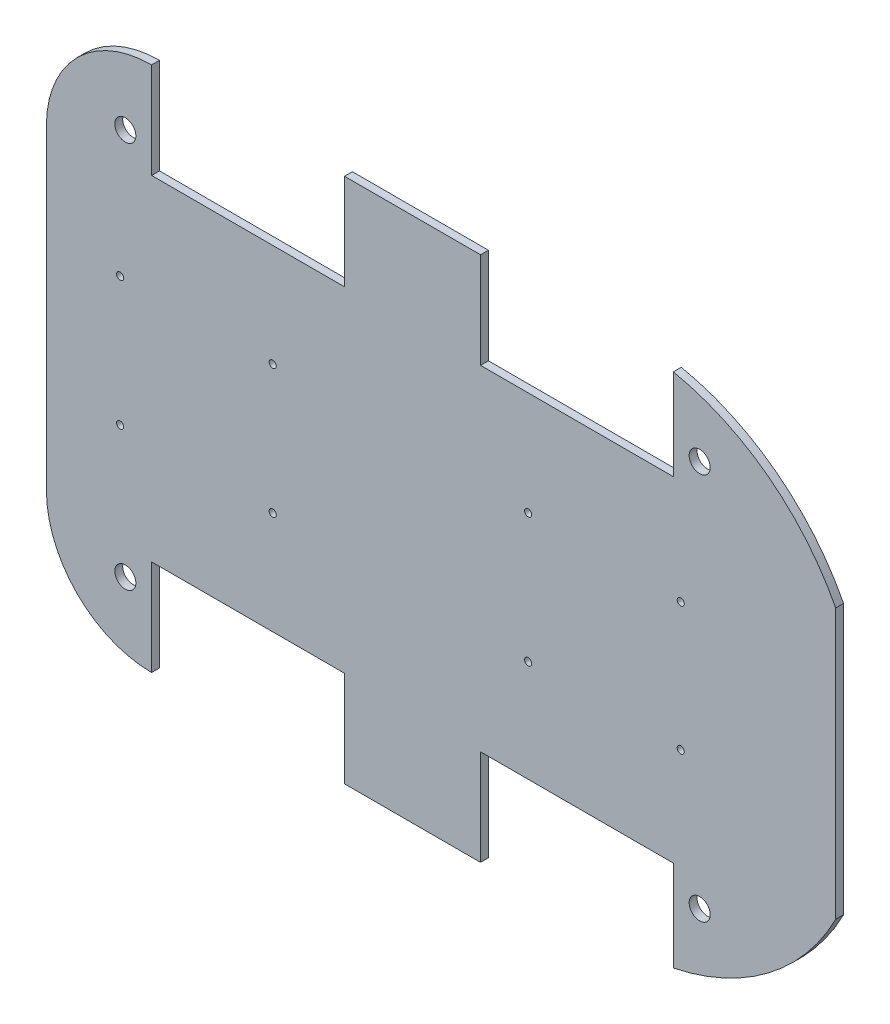
SolidWorks part; units mm, degrees
ref_plane "Front Plane" through (0, 0, 0) normal (0, 0, 1) x (1, 0, 0)
ref_plane "Top Plane" through (0, 0, 0) normal (0, 1, 0) x (1, 0, 0)
ref_plane "Right Plane" through (0, 0, 0) normal (1, 0, 0) x (0, 0, -1)
other "Configuration Table"
ref_plane "基准面1" through (0, 0, 3) normal (0, 0, 1) x (1, 0, 0)
sketch "草图1" plane through (0, 0, 3) normal (0, 0, 1) x (1, 0, 0)
  line L0 (63, 50.5) -> (48, 50.5)
  line L1 (48, 50.5) -> (48, 53.5)
  line L2 (48, 53.5) -> (63, 53.5)
  line L3 (63, 53.5) -> (63, 50.5)
  line L4 (188, 50.5) -> (173, 50.5)
  line L5 (173, 50.5) -> (173, 53.5)
  line L6 (173, 53.5) -> (188, 53.5)
  line L7 (188, 53.5) -> (188, 50.5)
  line L8 (188, 126.5) -> (173, 126.5)
  line L9 (173, 126.5) -> (173, 129.5)
  line L10 (173, 129.5) -> (188, 129.5)
  line L11 (188, 129.5) -> (188, 126.5)
  line L12 (63, 126.5) -> (48, 126.5)
  line L13 (48, 126.5) -> (48, 129.5)
  line L14 (48, 129.5) -> (63, 129.5)
  line L15 (63, 129.5) -> (63, 126.5)
  line L16 (165, 0) -> (165, 28)
  line L17 (165, 28) -> (173, 28)
  line L18 (173, 28) -> (173, 31.7)
  line L19 (173, 31.7) -> (188, 31.7)
  line L20 (188, 31.7) -> (188, 28)
  line L21 (188, 28) -> (238.3, 28)
  line L22 (238.3, 28) -> (238.3, 1.8801)
  line L23 (238.3, 178.1199) -> (238.3, 152)
  line L24 (238.3, 152) -> (188, 152)
  line L25 (188, 152) -> (188, 148.3)
  line L26 (188, 148.3) -> (173, 148.3)
  line L27 (173, 148.3) -> (173, 152)
  line L28 (173, 152) -> (165, 152)
  line L29 (165, 152) -> (165, 180)
  line L30 (165, 180) -> (113.3, 180)
  line L31 (113.3, 180) -> (113.3, 152)
  line L32 (113.3, 152) -> (63, 152)
  line L33 (63, 152) -> (63, 148.3)
  line L34 (63, 148.3) -> (48, 148.3)
  line L35 (48, 148.3) -> (48, 152)
  line L36 (48, 152) -> (40, 152)
  line L37 (40, 152) -> (40, 180)
  line L38 (0, 140) -> (0, 40)
  line L39 (40, 0) -> (40, 28)
  line L40 (40, 28) -> (48, 28)
  line L41 (48, 28) -> (48, 31.7)
  line L42 (48, 31.7) -> (63, 31.7)
  line L43 (63, 31.7) -> (63, 28)
  line L44 (63, 28) -> (113.3, 28)
  line L45 (113.3, 28) -> (113.3, 0)
  line L46 (113.3, 0) -> (165, 0)
  circle A0 centre (233.9, 84.9) radius 2
  circle A1 centre (186.1, 84.9) radius 2
  circle A2 centre (28, 166) radius 2
  circle A3 centre (28, 14) radius 2
  circle A4 centre (248.3, 165.0599) radius 2
  circle A5 centre (248.3, 14.9401) radius 2
  circle A6 centre (139.15, 14) radius 2
  circle A7 centre (139.15, 166) radius 2
  arc A8 (238.3, 1.8801) -> (238.3, 178.1199) centre (220, 90) ccw
  arc A9 (40, 180) -> (0, 140) centre (40, 140) ccw
  arc A10 (0, 40) -> (40, 0) centre (40, 40) ccw
extrude "凸台-拉伸1" add sketch "草图1" against normal blind 3
sketch "草图2" plane through (0, 0, 0) normal (0, 0, -1) x (-1, 0, 0)
  line L8 (-63, 129.5) -> (-48, 129.5) construction
  line L9 (-62.7801, 121.1) -> (-47.7801, 121.1)
  line L10 (-62.7801, 121.1) -> (-62.7801, 118.1)
  line L11 (-62.7801, 118.1) -> (-47.7801, 118.1)
  line L12 (-47.7801, 121.1) -> (-47.7801, 118.1)
  line L13 (-113.3, 152) -> (-63, 152) construction
  line L14 (-48, 152) -> (-40, 152) construction
  line L15 (-48, 148.3) -> (-48, 152) construction
  line L16 (-63, 148.3) -> (-48, 148.3) construction
  line L17 (-63, 152) -> (-63, 148.3) construction
  line L18 (-48, 152) -> (-40, 152)
  line L19 (-48, 148.3) -> (-48, 152)
  line L20 (-63, 148.3) -> (-48, 148.3)
  line L21 (-63, 152) -> (-63, 148.3)
  line L22 (-113.3, 152) -> (-63, 152)
  line L23 (-113.3, 152) -> (-113.3, 143.6)
  line L24 (-113.3, 143.6) -> (-63, 143.6)
  line L25 (-40, 143.6) -> (-40, 152)
  line L26 (-63, 143.6) -> (-63, 139.9)
  line L27 (-63, 139.9) -> (-48, 139.9)
  line L28 (-48, 139.9) -> (-48, 143.6)
  line L29 (-48, 143.6) -> (-40, 143.6)
  point P18 (-55.5, 139.9)
  dimension "D1" = 3
  dimension "D2" = 15
  dimension "D3" = 8.4
  dimension "D4" = 8.4
  dimension "D5" = 8.4
extrude "切除-拉伸1" cut sketch "草图2" against normal up to next
sketch "草图3" plane through (0, 0, 3) normal (0, 0, 1) x (1, 0, 0)
  circle A0 centre (186.1, 84.9) radius 2 construction
  circle A1 centre (233.9, 84.9) radius 2 construction
  circle A2 centre (186.1, 84.9) radius 2
  circle A3 centre (233.9, 84.9) radius 2
extrude "凸台-拉伸2" add sketch "草图3" against normal up to surface (3 mm away) up to face at (55.2801, 119.6, 0)
sketch "草图4" plane through (0, 0, 0) normal (0, 0, -1) x (-1, 0, 0)
  line L1 (-188.1856, 121.1) -> (-173.1856, 121.1)
  line L2 (-188.1856, 121.1) -> (-188.1856, 118.1)
  line L3 (-188.1856, 118.1) -> (-173.1856, 118.1)
  line L4 (-173.1856, 121.1) -> (-173.1856, 118.1)
  line L6 (-173, 126.5) -> (-188, 126.5) construction
  line L7 (-238.3, 143.6) -> (-188, 143.6)
  line L8 (-188, 143.6) -> (-188, 139.9)
  line L9 (-188, 139.9) -> (-173, 139.9)
  line L10 (-173, 139.9) -> (-173, 143.6)
  line L11 (-173, 143.6) -> (-165, 143.6)
  line L12 (-238.3, 152) -> (-238.3, 143.6)
  line L13 (-165, 152) -> (-165, 143.6)
  line L14 (-173, 152) -> (-165, 152) construction
  line L15 (-173, 148.3) -> (-173, 152) construction
  line L16 (-188, 148.3) -> (-173, 148.3) construction
  line L17 (-188, 152) -> (-188, 148.3) construction
  line L18 (-238.3, 152) -> (-188, 152) construction
  line L19 (-173, 152) -> (-165, 152)
  line L20 (-173, 148.3) -> (-173, 152)
  line L21 (-188, 148.3) -> (-173, 148.3)
  line L22 (-188, 152) -> (-188, 148.3)
  line L23 (-238.3, 152) -> (-188, 152)
  dimension "D1" = 15
  dimension "D2" = 3
  dimension "D3" = 8.4
  dimension "D4" = 8.4
  dimension "D5" = 8.4
  dimension "D6" = 8.4
  dimension "D7" = 0
  dimension "D8" = 0
extrude "切除-拉伸2" cut sketch "草图4" against normal blind 10
ref_plane "基准面2" through (0, 90, 0) normal (0, 1, 0) x (1, 0, 0)
split "分割4" trim tools "基准面2" bodies to split 106 resulting bodies 113
ref_plane "基准面3" through (139.15, 0, 0) normal (1, 0, 0) x (0, 0, -1)
sketch "草图9" plane through (0, 0, 0) normal (0, 0, -1) x (-1, 0, 0)
  line L2 (-310, 80) -> (0, 80)
  line L3 (0, 80) -> (0, 140)
  line L5 (-113.3, 180) -> (-113.3, 143.6)
  line L6 (-113.3, 143.6) -> (-40, 143.6)
  line L7 (-40, 143.6) -> (-40, 180)
  line L8 (-165, 180) -> (-165, 143.6)
  line L9 (-165, 143.6) -> (-238.3, 143.6)
  line L10 (-238.3, 143.6) -> (-238.3, 178.1199)
  line L11 (-113.3, 180) -> (-165, 180)
  line L12 (0, 140) -> (0, 90) construction
  line L15 (-310, 90) -> (-310, 80)
  arc A2 (0, 140) -> (-40, 180) centre (-40, 140) ccw construction
  arc A3 (0, 140) -> (-40, 180) centre (-40, 140) ccw
  arc A5 (-238.3, 178.1199) -> (-310, 90) centre (-220, 90) ccw construction
  arc A6 (-238.3, 178.1199) -> (-310, 90) centre (-220, 90) ccw
  dimension "D1" = 100
extrude "凸台-拉伸3" add sketch "草图9" against normal up to surface (3 mm away) up to face at (124.9777, 145.6603, 3)
sketch "草图10" plane through (0, 0, 0) normal (0, 0, -1) x (-1, 0, 0)
  line L0 (-238.3, 178.1199) -> (-238.3, 143.6) construction
  line L1 (-40, 143.6) -> (-40, 180) construction
  line L2 (-238.3, 143.6) -> (-165, 143.6) construction
  line L3 (-113.3, 143.6) -> (-40, 143.6) construction
  circle A0 centre (-248.3, 153.6) radius 4
  circle A1 centre (-30, 153.6) radius 4
  dimension "D1" = 8
  dimension "D2" = 8
  dimension "D3" = 10
  dimension "D4" = 10
  dimension "D5" = 10
  dimension "D6" = 10
extrude "切除-拉伸3" cut sketch "草图10" against normal up to surface (3 mm away) up to face at (145.048, 141.9622, 3)
mirror "镜向2" about plane through (310, 80, 328.7299) normal (0, -1, 0) of bodies 123
sketch "草图11" plane through (0, 0, 0) normal (0, 0, -1) x (-1, 0, 0)
  circle A0 centre (-86.0227, 104.5) radius 1.35 construction
  circle A1 centre (-86.0227, 55.5) radius 1.35 construction
  circle A2 centre (-28.0227, 104.5) radius 1.35 construction
  circle A3 centre (-28.0227, 55.5) radius 1.35 construction
  circle A12 centre (-86.0227, 104.5) radius 1.35
  circle A13 centre (-86.0227, 55.5) radius 1.35
  circle A14 centre (-28.0227, 104.5) radius 1.35
  circle A15 centre (-28.0227, 55.5) radius 1.35
extrude "切除-拉伸4" cut sketch "草图11" against normal up to surface (3 mm away) up to face at (252.3, 153.6, 3)
sketch "草图12" plane through (0, 0, 0) normal (0, 0, -1) x (-1, 0, 0)
  circle A0 centre (-86.0227, 104.5) radius 1.35 construction
  circle A1 centre (-28.0227, 104.5) radius 1.35 construction
  circle A2 centre (-28.0227, 55.5) radius 1.35 construction
  circle A3 centre (-86.0227, 55.5) radius 1.35 construction
  circle A12 centre (-28.0227, 55.5) radius 1.35
  circle A13 centre (-86.0227, 55.5) radius 1.35
  circle A14 centre (-28.0227, 104.5) radius 1.35
  circle A15 centre (-86.0227, 104.5) radius 1.35
  circle A16 centre (-86.0227, 104.5) radius 4
  circle A17 centre (-28.0227, 104.5) radius 4
  circle A18 centre (-28.0227, 55.5) radius 4
  circle A19 centre (-86.0227, 55.5) radius 4
  dimension "D1" = 8
  dimension "D2" = 8
  dimension "D3" = 8
  dimension "D4" = 8
extrude "凸台-拉伸4" add sketch "草图12" along normal blind 4
sketch "草图13" plane through (0, 0, 0) normal (0, 0, -1) x (-1, 0, 0)
  circle A0 centre (-183.0929, 55.1039) radius 1.35 construction
  circle A1 centre (-183.0929, 104.1039) radius 1.35 construction
  circle A2 centre (-241.0921, 103.8) radius 1.35 construction
  circle A3 centre (-241.0929, 55.1039) radius 1.35 construction
  circle A4 centre (-183.0929, 55.1039) radius 1.35
  circle A5 centre (-183.0929, 104.1039) radius 1.35
  circle A6 centre (-241.0921, 103.8) radius 1.35
  circle A7 centre (-241.0929, 55.1039) radius 1.35
extrude "切除-拉伸5" cut sketch "草图13" against normal up to surface (3 mm away) up to face at (87.3727, 55.5, 3)
sketch "草图14" plane through (0, 0, 0) normal (0, 0, -1) x (-1, 0, 0)
  circle A0 centre (-183.0929, 55.1039) radius 1.35 construction
  circle A1 centre (-241.0929, 55.1039) radius 1.35 construction
  circle A2 centre (-183.0929, 104.1039) radius 1.35 construction
  circle A3 centre (-241.0921, 103.8) radius 1.35 construction
  circle A4 centre (-183.0929, 55.1039) radius 1.35
  circle A5 centre (-241.0929, 55.1039) radius 1.35
  circle A6 centre (-183.0929, 104.1039) radius 1.35
  circle A7 centre (-241.0921, 103.8) radius 1.35
  circle A8 centre (-241.0921, 103.8) radius 4
  circle A9 centre (-183.0929, 104.1039) radius 4
  circle A10 centre (-241.0929, 55.1039) radius 4
  circle A11 centre (-183.0929, 55.1039) radius 4
  dimension "D1" = 8
  dimension "D2" = 8
  dimension "D3" = 8
  dimension "D4" = 8
extrude "凸台-拉伸5" add sketch "草图14" along normal blind 4
sketch "草图15" plane through (0, 0, 0) normal (0, 0, -1) x (-1, 0, 0)
  line L0 (-300, 131.2311) -> (-300, 28.7689) construction
  line L1 (-300, 131.2311) -> (-300, 28.7689)
  line L16 (-40, 180) -> (-40, 143.6)
  line L17 (-40, 143.6) -> (-113.3, 143.6)
  line L18 (-113.3, 143.6) -> (-113.3, 180)
  line L19 (-113.3, 180) -> (-165, 180)
  line L20 (-165, 180) -> (-165, 143.6)
  line L21 (-165, 143.6) -> (-238.3, 143.6)
  line L22 (-238.3, 143.6) -> (-238.3, 178.1199)
  line L23 (-310, 90) -> (-310, 70)
  line L24 (-238.3, -18.1199) -> (-238.3, 16.4)
  line L25 (-238.3, 16.4) -> (-165, 16.4)
  line L26 (-165, 16.4) -> (-165, -20)
  line L27 (-165, -20) -> (-113.3, -20)
  line L28 (-113.3, -20) -> (-113.3, 16.4)
  line L29 (-113.3, 16.4) -> (-40, 16.4)
  line L30 (-40, 16.4) -> (-40, -20)
  line L31 (0, 20) -> (0, 140)
  line L39 (-310, 90) -> (-310, 70)
  arc A4 (-238.3, 178.1199) -> (-310, 90) centre (-220, 90) ccw
  arc A5 (-310, 70) -> (-238.3, -18.1199) centre (-220, 70) ccw
  arc A6 (-40, -20) -> (0, 20) centre (-40, 20) ccw
  arc A7 (0, 140) -> (-40, 180) centre (-40, 140) ccw
  arc A8 (-300, 131.2311) -> (-310, 90) centre (-220, 90) ccw
  arc A9 (-310, 70) -> (-300, 28.7689) centre (-220, 70) ccw
  dimension "D1" = 0
extrude "切除-拉伸6" cut sketch "草图15" against normal blind 4
